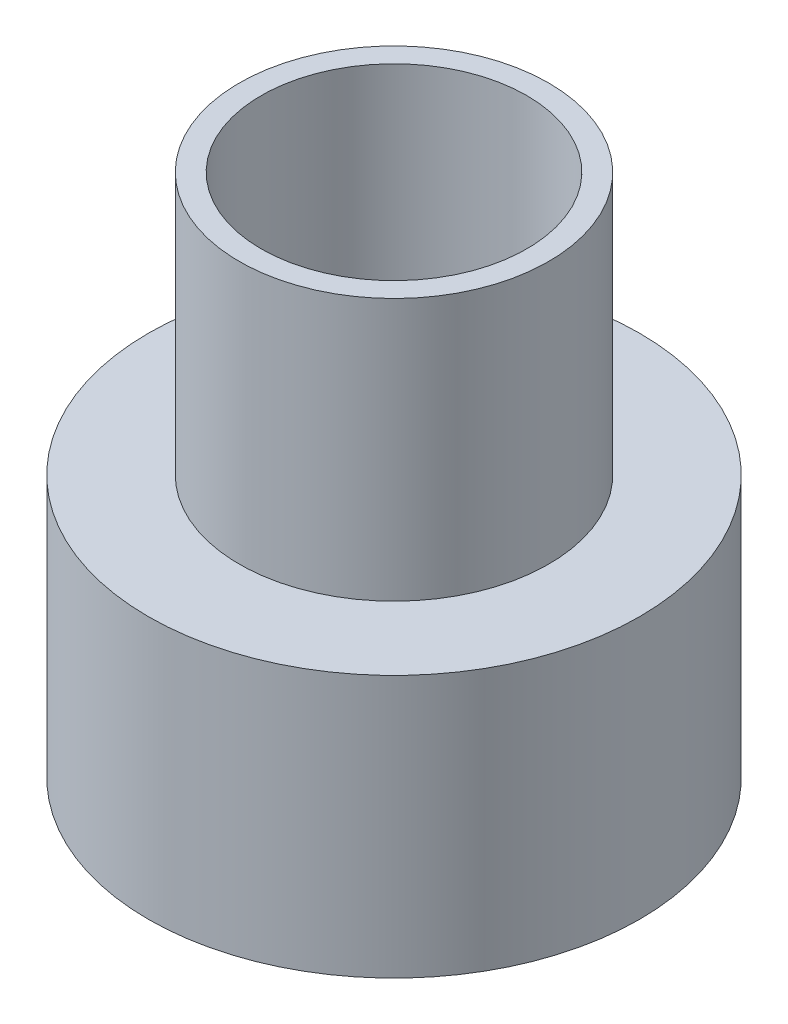
SolidWorks part; units mm, degrees
ref_plane "Front Plane" through (0, 0, 0) normal (0, 0, 1) x (1, 0, 0)
ref_plane "Top Plane" through (0, 0, 0) normal (0, 1, 0) x (1, 0, 0)
ref_plane "Right Plane" through (0, 0, 0) normal (1, 0, 0) x (0, 0, -1)
sketch "Sketch1" plane through (0, 0, 0) normal (0, 0, 1) x (1, 0, 0)
  line L0 (-22.479, 38.1) -> (-22.479, 0)
  line L1 (55, 0) -> (-55, 0) construction
  line L2 (-22.479, 0) -> (-35.687, 0)
  line L3 (-35.687, 0) -> (-35.687, -38.1)
  line L4 (-35.687, -38.1) -> (-32.512, -38.1)
  line L5 (-32.512, -38.1) -> (-32.512, -3.175)
  line L6 (-32.512, -3.175) -> (-25.654, -3.175)
  line L7 (-19.304, -3.175) -> (-19.304, 38.1)
  line L8 (-19.304, 38.1) -> (-22.479, 38.1)
  line L9 (-25.654, -3.175) -> (-25.654, -8.255)
  line L10 (0, -55) -> (0, 55) construction
  line L11 (0, -55.8394) -> (0, 96.5606) construction
  line L12 (-25.654, -8.255) -> (-22.479, -8.255)
  line L13 (-22.479, -8.255) -> (-22.479, -3.175)
  line L14 (-22.479, -3.175) -> (-19.304, -3.175)
  dimension "D1" = 3.175
  dimension "D2" = 3.175
  dimension "D3" = 3.175
  dimension "D4" = 38.1
  dimension "D7" = 19.304
  dimension "D8" = 152.4
  dimension "D9" = 5.08
  dimension "D10" = 3.175
  dimension "D6" = 32.512
revolve "Revolve1" add sketch "Sketch1" angle 360 about L11
equation "\"lowerOD\"= 3.85"
equation "\"upperOD\"= 2in"
equation "\"tubeLength\"= 2in"
equation "\"wallThickness\"= 1 / 8in"
equation "\"length\"= 3.5"
equation "\"D1@Sketch1\"=\"wallThickness\""
equation "\"D2@Sketch1\"=\"wallThickness\""
equation "\"D3@Sketch1\"=\"wallThickness\""
equation "\"D4@Sketch1\"=1.5"
equation "\"D7@Sketch1\"=1.52/2in"
equation "\"D10@Sketch1\"=\"wallThickness\""
